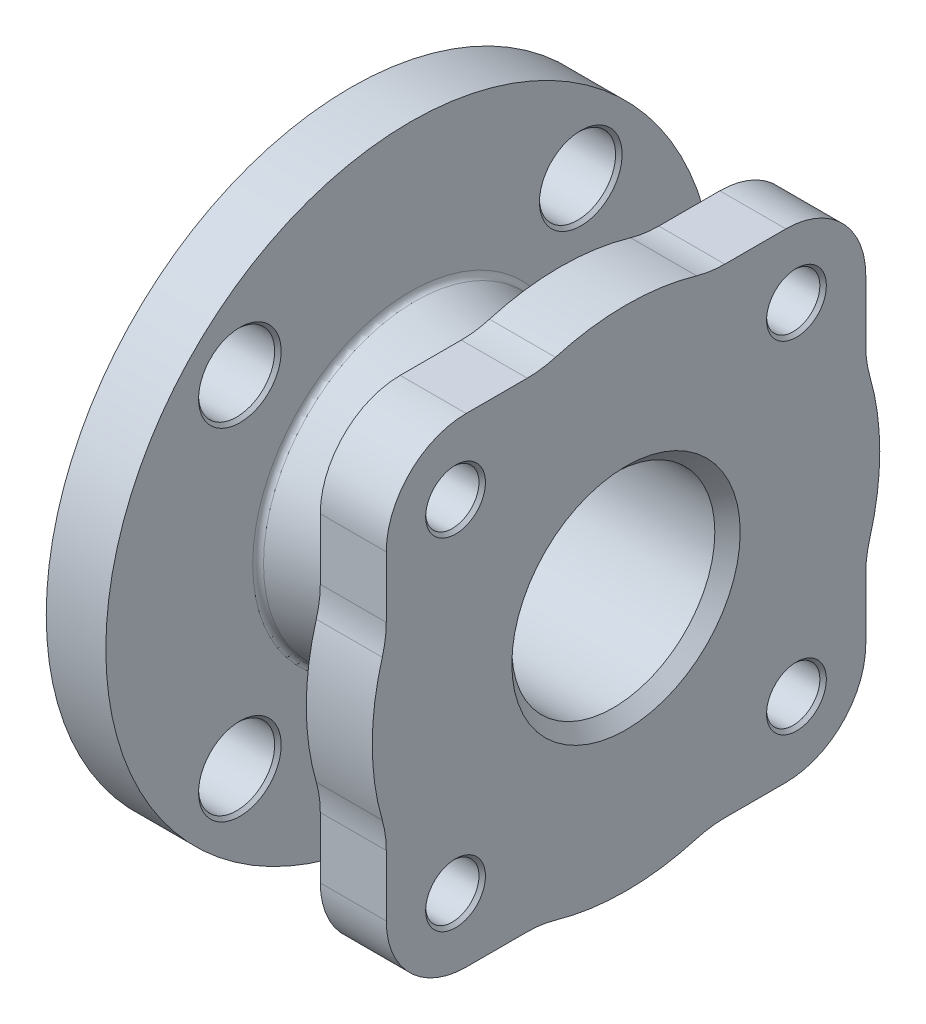
SolidWorks part; units mm, degrees
ref_plane "Front Plane" through (0, 0, 0) normal (0, 0, 1) x (1, 0, 0)
ref_plane "Top Plane" through (0, 0, 0) normal (0, 1, 0) x (1, 0, 0)
ref_plane "Right Plane" through (0, 0, 0) normal (1, 0, 0) x (0, 0, -1)
sketch "Sketch1" plane through (0, 0, 0) normal (0, 0, 1) x (1, 0, 0)
  line L0 (0, 25.4) -> (53.975, 25.4)
  line L1 (53.975, 25.4) -> (53.975, 47.625)
  line L2 (53.975, 47.625) -> (52.3748, 46.0248)
  line L3 (52.3748, 46.0248) -> (52.3748, 34.29)
  line L4 (52.3748, 34.29) -> (34.925, 34.29)
  line L5 (34.925, 34.29) -> (16.51, 38.2042)
  line L6 (16.51, 38.2042) -> (16.51, 76.2)
  line L7 (16.51, 76.2) -> (1.6002, 76.2)
  line L8 (1.6002, 76.2) -> (1.6002, 47.6377)
  line L9 (1.6002, 47.6377) -> (0, 46.0375)
  line L11 (0, 46.0375) -> (0, 25.4)
  line L12 (0, 25.4) -> (0, 0) construction
  line L13 (0, 0) -> (61.8118, 0) construction
  dimension "D1" = 53.975
  dimension "D2" = 50.8
  dimension "D3" = 95.25
  dimension "D4" = 1.6002
  dimension "D5" = 45
  dimension "D6" = 68.58
  dimension "D7" = 12
  dimension "D8" = 34.925
  dimension "D9" = 16.51
  dimension "D10" = 1.6002
  dimension "D11" = 45
  dimension "D12" = 152.4
  dimension "D13" = 92.075
revolve "Revolve1" add sketch "Sketch1" angle 360 about L13
sketch "Sketch2" plane through (53.975, 0, 0) normal (1, 0, 0) x (0, 0, -1)
  line L0 (0, 0) -> (0, 25.4) construction
  line L1 (0, 0) -> (-42.6562, 42.6562) construction
  line L2 (-42.6562, 42.6562) -> (-37.3538, 37.3538) construction
  line L3 (0, 0) -> (42.6562, 42.6562) construction
  line L4 (0, 0) -> (42.6562, -42.6562) construction
  line L5 (0, 0) -> (-42.6562, -42.6562) construction
  line L6 (-40.005, 59.9948) -> (-40.005, 40.005) construction
  line L7 (-40.005, 40.005) -> (-59.9948, 40.005) construction
  line L8 (-59.9948, 40.005) -> (-59.9948, 24.7172)
  line L9 (-40.005, 59.9948) -> (-24.7172, 59.9948)
  line L10 (59.9948, 40.005) -> (59.9948, 24.7172)
  line L11 (40.005, 59.9948) -> (24.7172, 59.9948)
  line L12 (40.005, -59.9948) -> (24.7172, -59.9948)
  line L13 (59.9948, -40.005) -> (59.9948, -24.7172)
  line L14 (-59.9948, -40.005) -> (-59.9948, -24.7172)
  line L15 (-40.005, -59.9948) -> (-24.7172, -59.9948)
  arc A0 (-60.9963, 17.6551) -> (-60.9963, -17.6551) centre (0, 0) ccw
  circle A1 centre (0, 0) radius 60.325 construction
  circle A2 centre (0, 0) radius 25.4 construction
  arc A3 (17.6551, 60.9963) -> (-17.6551, 60.9963) centre (0, 0) ccw
  arc A4 (-40.005, 59.9948) -> (-59.9948, 40.005) centre (-40.005, 40.005) ccw
  arc A7 (-59.9948, -40.005) -> (-40.005, -59.9948) centre (-40.005, -40.005) ccw
  arc A8 (59.9948, 40.005) -> (40.005, 59.9948) centre (40.005, 40.005) ccw
  arc A9 (54.3798, 26.1141) -> (56.5787, 28.8289) centre (40.005, 40.005) ccw [skipped]
  arc A10 (60.9963, -17.6551) -> (60.9963, 17.6551) centre (0, 0) ccw
  arc A11 (40.005, -59.9948) -> (59.9948, -40.005) centre (40.005, -40.005) ccw
  arc A12 (56.5787, -28.8289) -> (54.3798, -26.1141) centre (40.005, -40.005) ccw [skipped]
  arc A13 (-17.6551, -60.9963) -> (17.6551, -60.9963) centre (0, 0) ccw
  arc A14 (-24.7172, 59.9948) -> (-17.6551, 60.9963) centre (-24.7172, 85.3948) ccw
  arc A15 (24.7172, 59.9948) -> (17.6551, 60.9963) centre (24.7172, 85.3948) cw
  arc A16 (59.9948, 24.7172) -> (60.9963, 17.6551) centre (85.3948, 24.7172) ccw
  arc A17 (59.9948, -24.7172) -> (60.9963, -17.6551) centre (85.3948, -24.7172) cw
  arc A18 (24.7172, -59.9948) -> (17.6551, -60.9963) centre (24.7172, -85.3948) ccw
  arc A19 (-24.7172, -59.9948) -> (-17.6551, -60.9963) centre (-24.7172, -85.3948) cw
  arc A20 (-59.9948, -24.7172) -> (-60.9963, -17.6551) centre (-85.3948, -24.7172) ccw
  arc A21 (-59.9948, 24.7172) -> (-60.9963, 17.6551) centre (-85.3948, 24.7172) cw
  circle A22 centre (-42.6562, 42.6562) radius 6.6675
  circle A23 centre (42.6562, 42.6562) radius 6.6675
  circle A24 centre (42.6562, -42.6562) radius 6.6675
  circle A25 centre (-42.6562, -42.6562) radius 6.6675
  point P23 (0, 0)
  point P38 (0, 0)
  point P65 (0, 0)
  circle M38 centre (0, 0) radius 47.625
  circle M39 centre (0, 0) radius 25.4
  dimension "D1" = 127
  dimension "D2" = 120.65
  dimension "D4" = 40.005
  dimension "D8" = 25.4
  dimension "D9" = 4
  dimension "D3" = 45
  dimension "D5" = 40.005
  dimension "D6" = 4
  dimension "D7" = 4
extrude "Boss-Extrude1" add sketch "Sketch2" along normal blind 16.51 contours L8 A21 A0 A20 L14 A7 L15 A19 A13 A18 L12 A11 L13 A17 A10 A16 L10 A8 L11 A15 A3 A14 L9 A4 A25 A24 A23 A22 M38 | M38 M39
sketch "Sketch3" plane through (1.6002, 0, 0) normal (-1, 0, 0) x (0, 0, 1)
  line L0 (0, 0) -> (-42.6562, -42.6562) construction
  line L1 (0, 0) -> (42.6562, -42.6562) construction
  line L2 (0, 0) -> (42.6562, 42.6562) construction
  line L3 (0, 0) -> (-42.6562, 42.6562) construction
  line L4 (0, 0) -> (-42.6562, -42.6562) construction
  line L5 (0, 0) -> (42.6562, -42.6562) construction
  line L6 (0, 0) -> (42.6562, 42.6562) construction
  line L7 (0, 0) -> (-42.6562, 42.6562) construction
  line L8 (0, 0) -> (42.6562, 42.6562) construction
  line L9 (0, 0) -> (42.6562, -42.6562) construction
  line L10 (0, 0) -> (-42.6562, -42.6562) construction
  circle A0 centre (0, 0) radius 60.325 construction
  circle A1 centre (0, 0) radius 60.325 construction
  circle A2 centre (-42.6562, 42.6562) radius 9.525
  circle A3 centre (42.6562, 42.6562) radius 9.525
  circle A4 centre (42.6562, -42.6562) radius 9.525
  circle A5 centre (-42.6562, -42.6562) radius 9.525
  point P19 (0, 0)
  dimension "D1" = 19.05
  dimension "D2" = 4
extrude "Cut-Extrude1" cut sketch "Sketch3" against normal up to next contours A5 | A2 | A3 | A4
chamfer "Chamfer1" distance 0.8128 angle 45 8 edges at (53.975, 42.6562, -49.3237) (70.485, 42.6562, -49.3237) (53.975, -42.6562, -49.3237) (70.485, -42.6562, -49.3237) (53.975, -42.6562, 35.9887) (70.485, -42.6562, 35.9887) (53.975, 42.6562, 35.9887) (70.485, 42.6562, 35.9887)
chamfer "Chamfer2" distance 0.8128 angle 45 8 edges at (16.51, -42.6562, -33.1312) (1.6002, -42.6562, -33.1312) (16.51, -42.6562, 52.1812) (1.6002, -42.6562, 52.1812) (16.51, 42.6562, 52.1812) (1.6002, 42.6562, 52.1812) (16.51, 42.6562, -33.1312) (1.6002, 42.6562, -33.1312)
chamfer "Chamfer3" distance 3.175 angle 45 2 edges at (70.485, 0, -25.4) (0, 0, 25.4)
fillet "Fillet2" radius 1.524 2 edges at (16.51, 0, 38.2042) (52.3748, 0, 34.29)
